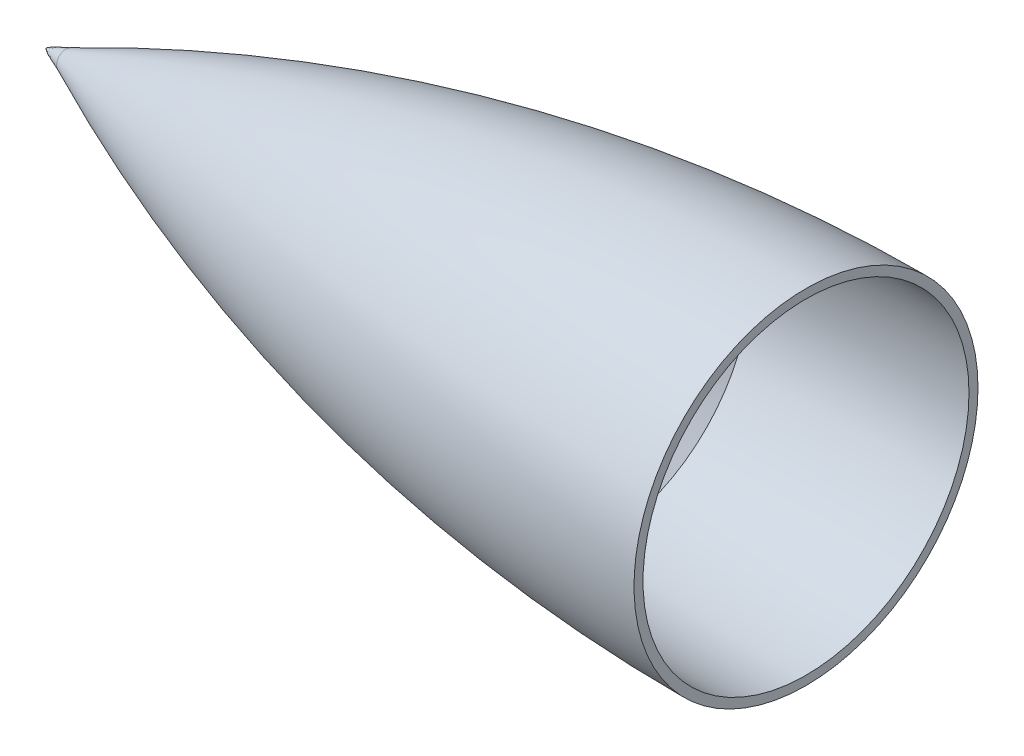
SolidWorks part; units mm, degrees
ref_plane "Front Plane" through (0, 0, 0) normal (0, 0, 1) x (1, 0, 0)
ref_plane "Top Plane" through (0, 0, 0) normal (0, 1, 0) x (1, 0, 0)
ref_plane "Right Plane" through (0, 0, 0) normal (1, 0, 0) x (0, 0, -1)
sketch "Sketch2" plane through (0, 0, 0) normal (0, 0, 1) x (1, 0, 0)
  line L0 (0, 441.2674) -> (0, 439.0174) construction
  line L1 (0, 441.2674) -> (0, 439.0174)
  line L2 (-178.0795, 398.2674) -> (-190, 398.2674)
  line L12 (-53.2932, 434.3819) -> (-53.2932, 438.0374) construction
  line L20 (-190, 398.2674) -> (-231.9218, 398.2674) construction
  line L21 (-190, 398.2674) -> (-178.0795, 398.2674) construction
  line L23 (-51.7141, 435.961) -> (-54.8722, 432.8029)
  arc A0 (0, 441.2674) -> (-190, 398.2674) centre (0, 0) ccw
  arc A3 (0, 439.0174) -> (-51.7141, 435.961) centre (0, 0) ccw
  arc A8 (-54.8722, 432.8029) -> (-178.0795, 398.2674) centre (0, 0) ccw
  dimension "D1" = 190
  dimension "D3" = 5
  dimension "D4" = 11.9205
  dimension "D2" = 2.25
  dimension "D5" = 45
revolve "Revolve3" add sketch "Sketch2" angle 360 about L20
sketch "Sketch3" plane through (0, 0, 0) normal (0, 0, 1) x (1, 0, 0)
  line L0 (-190, 398.2674) -> (-185, 398.2674)
  line L1 (-185, 398.2674) -> (-185, 400.6145)
  arc A0 (0, 441.2674) -> (-190, 398.2674) centre (0, 0) ccw construction
  arc A1 (-185, 400.6145) -> (-190, 398.2674) centre (0, 0) ccw
  dimension "D1" = 5
revolve "Cut-Revolve3" cut sketch "Sketch3" angle 360 about L0
sketch "Sketch4" plane through (0, 0, 0) normal (0, 0, 1) x (1, 0, 0)
  line L0 (-185, 398.2674) -> (-189.991, 398.2674)
  line L2 (2.5, -1.1735) -> (-2.5, -1.1735)
  line L3 (2.5, -1.1735) -> (2.5, 1.1735)
  line L4 (2.5, -1.1735) -> (-2.5, -1.1735)
  line L5 (2.5, -1.1735) -> (2.5, 1.1735)
  line L8 (-185, 400.6145) -> (-185, 395.9204) construction
  line L9 (-185, 398.2674) -> (-185, 400.6145)
  spline S0 degree 3 poles (2.5, 1.1735) (-0.7043, -0.033) (-2.4355, -0.6033) (-2.5, -1.1735) knots 0 0 0 0 0.5 0.5 0.5 0.5
  spline S1 degree 3 poles (2.5, 1.1735) (-0.7043, -0.033) (-2.4355, -0.6033) (-2.5, -1.1735) knots 0 0 0 0 0.5 0.5 0.5 0.5
  spline S2 degree 3 poles (-185, 400.6145) (-186.9943, 399.7724) (-189.3345, 399.0591) (-189.991, 398.2674) knots 0 0 0 0 1 1 1 1
  dimension "D2" = 5
  dimension "D3" = 5
revolve "Revolve4" add sketch "Sketch4" angle 360 about L0
